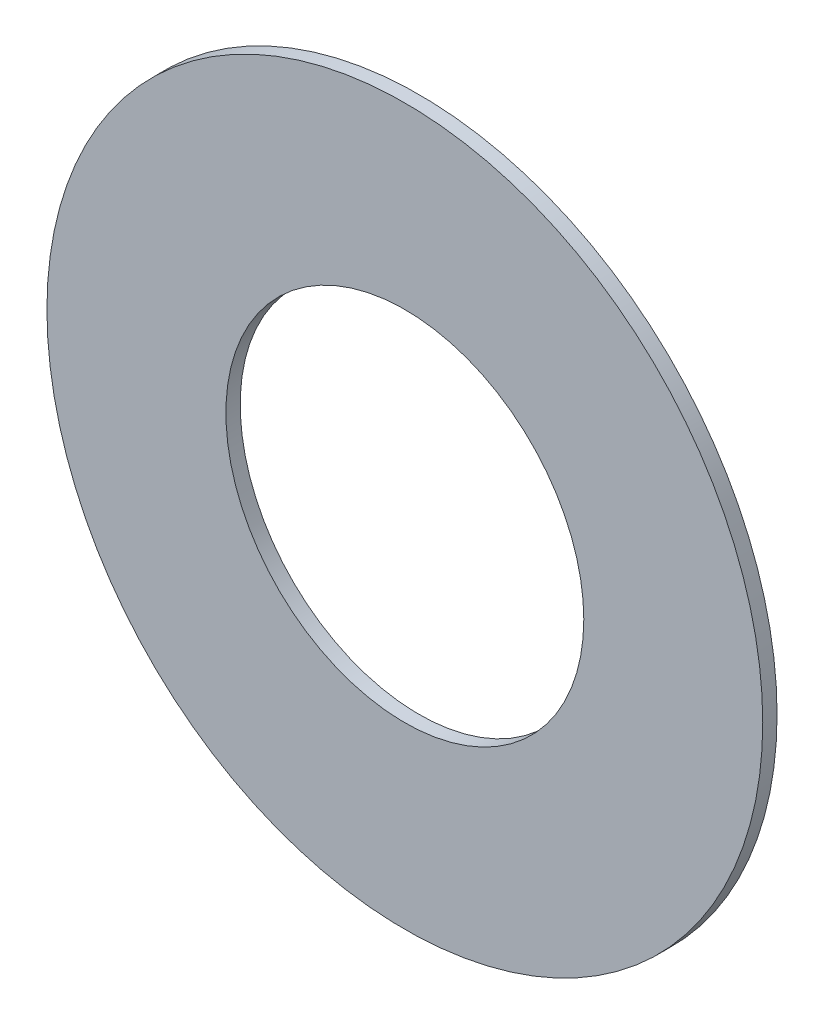
SolidWorks part; units mm, degrees
ref_plane "前视基准面" through (0, 0, 0) normal (0, 0, 1) x (1, 0, 0)
ref_plane "上视基准面" through (0, 0, 0) normal (0, 1, 0) x (1, 0, 0)
ref_plane "右视基准面" through (0, 0, 0) normal (1, 0, 0) x (0, 0, -1)
other "Configuration Table"
sketch "Sketch1" plane through (0, 0, 0) normal (0, 0, 1) x (1, 0, 0)
  circle A0 centre (0, 0) radius 50
  circle A1 centre (0, 0) radius 25
extrude "Boss-Extrude1" add sketch "Sketch1" along normal blind 2
